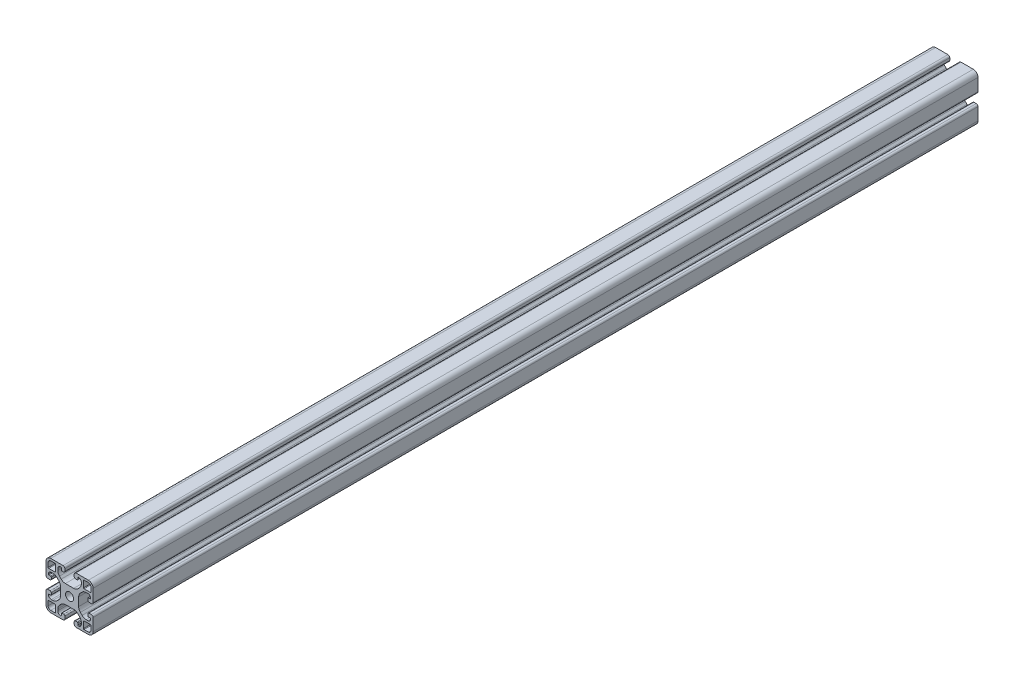
SolidWorks part; units mm, degrees
ref_plane "Plan de face" through (0, 0, 0) normal (0, 0, 1) x (1, 0, 0)
ref_plane "Plan de dessus" through (0, 0, 0) normal (0, 1, 0) x (1, 0, 0)
ref_plane "Plan de droite" through (0, 0, 0) normal (1, 0, 0) x (0, 0, -1)
ref_plane "Plan1" through (0, 0, -30) normal (0, 0, -1) x (-1, 0, 0)
sketch "Esquisse1" plane through (0, 0, -30) normal (0, 0, -1) x (-1, 0, 0)
  line L0 (-4.5, 15) -> (-4.5, 13.5)
  line L1 (-4, 13) -> (-2.5, 13)
  line L2 (-4.5, 10) -> (-5.8076, 10)
  line L3 (-9.3431, 11.4645) -> (-10.7855, 12.9069)
  line L4 (-12.25, 16.4424) -> (-12.25, 23.5576)
  line L5 (-10.7855, 27.0931) -> (-9.3431, 28.5355)
  line L6 (-5.8076, 30) -> (-4.5, 30)
  line L7 (-2.5, 27) -> (-4, 27)
  line L8 (-4.5, 26.5) -> (-4.5, 25)
  line L9 (-3.5, 24) -> (-1.5, 24)
  line L10 (0, 25.5) -> (0, 36)
  line L11 (-4, 40) -> (-14.5, 40)
  line L12 (-16, 38.5) -> (-16, 36.5)
  line L13 (-15, 35.5) -> (-13.5, 35.5)
  line L14 (-13, 36) -> (-13, 37.5)
  line L15 (-10, 35.5) -> (-10, 34.1924)
  line L16 (-11.4645, 30.6569) -> (-12.9069, 29.2145)
  line L17 (-16.4424, 27.75) -> (-23.5576, 27.75)
  line L18 (-27.0931, 29.2145) -> (-28.5355, 30.6569)
  line L19 (-30, 34.1924) -> (-30, 35.5)
  line L20 (-27, 37.5) -> (-27, 36)
  line L21 (-26.5, 35.5) -> (-25, 35.5)
  line L22 (-24, 36.5) -> (-24, 38.5)
  line L23 (-25.5, 40) -> (-36, 40)
  line L24 (-40, 36) -> (-40, 25.5)
  line L25 (-38.5, 24) -> (-36.5, 24)
  line L26 (-35.5, 25) -> (-35.5, 26.5)
  line L27 (-36, 27) -> (-37.5, 27)
  line L28 (-35.5, 30) -> (-34.1924, 30)
  line L29 (-30.6569, 28.5355) -> (-29.2145, 27.0931)
  line L30 (-27.75, 23.5576) -> (-27.75, 16.4424)
  line L31 (-29.2145, 12.9069) -> (-30.6569, 11.4645)
  line L32 (-34.1924, 10) -> (-35.5, 10)
  line L33 (-37.5, 13) -> (-36, 13)
  line L34 (-35.5, 13.5) -> (-35.5, 15)
  line L35 (-36.5, 16) -> (-38.5, 16)
  line L36 (-40, 14.5) -> (-40, 4)
  line L37 (-36, 0) -> (-25.5, 0)
  line L38 (-24, 1.5) -> (-24, 3.5)
  line L39 (-25, 4.5) -> (-26.5, 4.5)
  line L40 (-27, 4) -> (-27, 2.5)
  line L41 (-30, 4.5) -> (-30, 5.8076)
  line L42 (-28.5355, 9.3431) -> (-27.0931, 10.7855)
  line L43 (-23.5576, 12.25) -> (-16.4424, 12.25)
  line L44 (-12.9069, 10.7855) -> (-11.4645, 9.3431)
  line L45 (-10, 5.8076) -> (-10, 4.5)
  line L46 (-13, 2.5) -> (-13, 4)
  line L47 (-13.5, 4.5) -> (-15, 4.5)
  line L48 (-16, 3.5) -> (-16, 1.5)
  line L49 (-14.5, 0) -> (-4, 0)
  line L50 (0, 4) -> (0, 14.5)
  line L51 (-1.5, 16) -> (-3.5, 16)
  line L52 (-4, 1.8) -> (-7.7, 1.8)
  line L53 (-8.2, 2.3) -> (-8.2, 7.7)
  line L54 (-7.7, 8.2) -> (-2.3, 8.2)
  line L55 (-1.8, 7.7) -> (-1.8, 4)
  line L56 (-38.2, 4) -> (-38.2, 7.7)
  line L57 (-37.7, 8.2) -> (-32.3, 8.2)
  line L58 (-31.8, 7.7) -> (-31.8, 2.3)
  line L59 (-32.3, 1.8) -> (-36, 1.8)
  line L60 (-36, 38.2) -> (-32.3, 38.2)
  line L61 (-31.8, 37.7) -> (-31.8, 32.3)
  line L62 (-32.3, 31.8) -> (-37.7, 31.8)
  line L63 (-38.2, 32.3) -> (-38.2, 36)
  line L64 (-1.8, 36) -> (-1.8, 32.3)
  line L65 (-2.3, 31.8) -> (-7.7, 31.8)
  line L66 (-8.2, 32.3) -> (-8.2, 37.7)
  line L67 (-7.7, 38.2) -> (-4, 38.2)
  arc A0 (-4.5, 13.5) -> (-4, 13) centre (-4, 13.5) ccw
  arc A1 (-2.5, 13) -> (-2, 12.5) centre (-2.5, 12.5) cw
  arc A2 (-2, 12.5) -> (-4.5, 10) centre (-4.5, 12.5) cw
  arc A3 (-5.8076, 10) -> (-9.3431, 11.4645) centre (-5.8076, 15) cw
  arc A4 (-10.7855, 12.9069) -> (-12.25, 16.4424) centre (-7.25, 16.4424) cw
  arc A5 (-12.25, 23.5576) -> (-10.7855, 27.0931) centre (-7.25, 23.5576) cw
  arc A6 (-9.3431, 28.5355) -> (-5.8076, 30) centre (-5.8076, 25) cw
  arc A7 (-4.5, 30) -> (-2, 27.5) centre (-4.5, 27.5) cw
  arc A8 (-2, 27.5) -> (-2.5, 27) centre (-2.5, 27.5) cw
  arc A9 (-4, 27) -> (-4.5, 26.5) centre (-4, 26.5) ccw
  arc A10 (-4.5, 25) -> (-3.5, 24) centre (-3.5, 25) ccw
  arc A11 (-1.5, 24) -> (0, 25.5) centre (-1.5, 25.5) ccw
  arc A12 (0, 36) -> (-4, 40) centre (-4, 36) ccw
  arc A13 (-14.5, 40) -> (-16, 38.5) centre (-14.5, 38.5) ccw
  arc A14 (-16, 36.5) -> (-15, 35.5) centre (-15, 36.5) ccw
  arc A15 (-13.5, 35.5) -> (-13, 36) centre (-13.5, 36) ccw
  arc A16 (-13, 37.5) -> (-12.5, 38) centre (-12.5, 37.5) cw
  arc A17 (-12.5, 38) -> (-10, 35.5) centre (-12.5, 35.5) cw
  arc A18 (-10, 34.1924) -> (-11.4645, 30.6569) centre (-15, 34.1924) cw
  arc A19 (-12.9069, 29.2145) -> (-16.4424, 27.75) centre (-16.4424, 32.75) cw
  arc A20 (-23.5576, 27.75) -> (-27.0931, 29.2145) centre (-23.5576, 32.75) cw
  arc A21 (-28.5355, 30.6569) -> (-30, 34.1924) centre (-25, 34.1924) cw
  arc A22 (-30, 35.5) -> (-27.5, 38) centre (-27.5, 35.5) cw
  arc A23 (-27.5, 38) -> (-27, 37.5) centre (-27.5, 37.5) cw
  arc A24 (-27, 36) -> (-26.5, 35.5) centre (-26.5, 36) ccw
  arc A25 (-25, 35.5) -> (-24, 36.5) centre (-25, 36.5) ccw
  arc A26 (-24, 38.5) -> (-25.5, 40) centre (-25.5, 38.5) ccw
  arc A27 (-36, 40) -> (-40, 36) centre (-36, 36) ccw
  arc A28 (-40, 25.5) -> (-38.5, 24) centre (-38.5, 25.5) ccw
  arc A29 (-36.5, 24) -> (-35.5, 25) centre (-36.5, 25) ccw
  arc A30 (-35.5, 26.5) -> (-36, 27) centre (-36, 26.5) ccw
  arc A31 (-37.5, 27) -> (-38, 27.5) centre (-37.5, 27.5) cw
  arc A32 (-38, 27.5) -> (-35.5, 30) centre (-35.5, 27.5) cw
  arc A33 (-34.1924, 30) -> (-30.6569, 28.5355) centre (-34.1924, 25) cw
  arc A34 (-29.2145, 27.0931) -> (-27.75, 23.5576) centre (-32.75, 23.5576) cw
  arc A35 (-27.75, 16.4424) -> (-29.2145, 12.9069) centre (-32.75, 16.4424) cw
  arc A36 (-30.6569, 11.4645) -> (-34.1924, 10) centre (-34.1924, 15) cw
  arc A37 (-35.5, 10) -> (-38, 12.5) centre (-35.5, 12.5) cw
  arc A38 (-38, 12.5) -> (-37.5, 13) centre (-37.5, 12.5) cw
  arc A39 (-36, 13) -> (-35.5, 13.5) centre (-36, 13.5) ccw
  arc A40 (-35.5, 15) -> (-36.5, 16) centre (-36.5, 15) ccw
  arc A41 (-38.5, 16) -> (-40, 14.5) centre (-38.5, 14.5) ccw
  arc A42 (-40, 4) -> (-36, 0) centre (-36, 4) ccw
  arc A43 (-25.5, 0) -> (-24, 1.5) centre (-25.5, 1.5) ccw
  arc A44 (-24, 3.5) -> (-25, 4.5) centre (-25, 3.5) ccw
  arc A45 (-26.5, 4.5) -> (-27, 4) centre (-26.5, 4) ccw
  arc A46 (-27, 2.5) -> (-27.5, 2) centre (-27.5, 2.5) cw
  arc A47 (-27.5, 2) -> (-30, 4.5) centre (-27.5, 4.5) cw
  arc A48 (-30, 5.8076) -> (-28.5355, 9.3431) centre (-25, 5.8076) cw
  arc A49 (-27.0931, 10.7855) -> (-23.5576, 12.25) centre (-23.5576, 7.25) cw
  arc A50 (-16.4424, 12.25) -> (-12.9069, 10.7855) centre (-16.4424, 7.25) cw
  arc A51 (-11.4645, 9.3431) -> (-10, 5.8076) centre (-15, 5.8076) cw
  arc A52 (-10, 4.5) -> (-12.5, 2) centre (-12.5, 4.5) cw
  arc A53 (-12.5, 2) -> (-13, 2.5) centre (-12.5, 2.5) cw
  arc A54 (-13, 4) -> (-13.5, 4.5) centre (-13.5, 4) ccw
  arc A55 (-15, 4.5) -> (-16, 3.5) centre (-15, 3.5) ccw
  arc A56 (-16, 1.5) -> (-14.5, 0) centre (-14.5, 1.5) ccw
  arc A57 (-4, 0) -> (0, 4) centre (-4, 4) ccw
  arc A58 (0, 14.5) -> (-1.5, 16) centre (-1.5, 14.5) ccw
  arc A59 (-3.5, 16) -> (-4.5, 15) centre (-3.5, 15) ccw
  circle A60 centre (-20, 20) radius 3.4
  arc A61 (-1.8, 4) -> (-4, 1.8) centre (-4, 4) cw
  arc A62 (-7.7, 1.8) -> (-8.2, 2.3) centre (-7.7, 2.3) cw
  arc A63 (-8.2, 7.7) -> (-7.7, 8.2) centre (-7.7, 7.7) cw
  arc A64 (-2.3, 8.2) -> (-1.8, 7.7) centre (-2.3, 7.7) cw
  arc A65 (-36, 1.8) -> (-38.2, 4) centre (-36, 4) cw
  arc A66 (-38.2, 7.7) -> (-37.7, 8.2) centre (-37.7, 7.7) cw
  arc A67 (-32.3, 8.2) -> (-31.8, 7.7) centre (-32.3, 7.7) cw
  arc A68 (-31.8, 2.3) -> (-32.3, 1.8) centre (-32.3, 2.3) cw
  arc A69 (-38.2, 36) -> (-36, 38.2) centre (-36, 36) cw
  arc A70 (-32.3, 38.2) -> (-31.8, 37.7) centre (-32.3, 37.7) cw
  arc A71 (-31.8, 32.3) -> (-32.3, 31.8) centre (-32.3, 32.3) cw
  arc A72 (-37.7, 31.8) -> (-38.2, 32.3) centre (-37.7, 32.3) cw
  arc A73 (-4, 38.2) -> (-1.8, 36) centre (-4, 36) cw
  arc A74 (-1.8, 32.3) -> (-2.3, 31.8) centre (-2.3, 32.3) cw
  arc A75 (-7.7, 31.8) -> (-8.2, 32.3) centre (-7.7, 32.3) cw
  arc A76 (-8.2, 37.7) -> (-7.7, 38.2) centre (-7.7, 37.7) cw
extrude "Boss.-Extru.1" add sketch "Esquisse1" against normal blind 752
